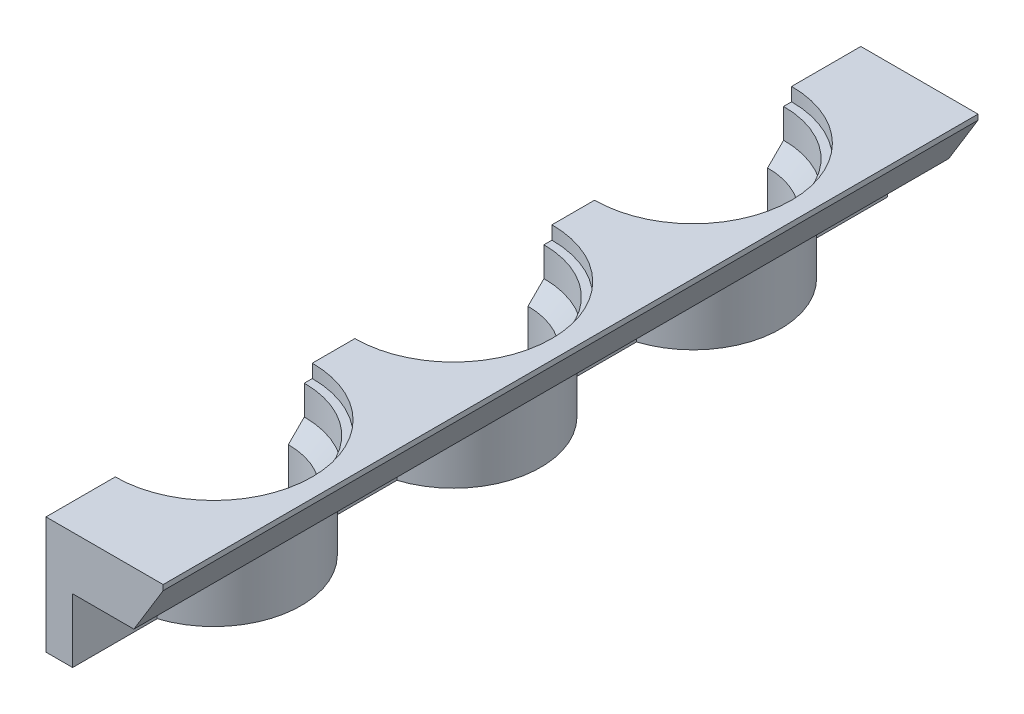
SolidWorks part; units mm, degrees
ref_plane "Płaszczyzna przednia" through (0, 0, 0) normal (0, 0, 1) x (1, 0, 0)
ref_plane "Płaszczyzna górna" through (0, 0, 0) normal (0, 1, 0) x (1, 0, 0)
ref_plane "Płaszczyzna prawa" through (0, 0, 0) normal (1, 0, 0) x (0, 0, -1)
sketch "Sketch1" plane through (0, 0, 0) normal (0, 1, 0) x (1, 0, 0)
  line L0 (0, 65.8555) -> (0, -65.8555) construction
  line L1 (0, -11.4) -> (0, -31.5)
  line L2 (0, -31.5) -> (22, -31.5)
  line L3 (104.3478, 45) -> (-104.3478, 45) construction
  line L4 (22, -31.5) -> (22, 121.5)
  line L5 (0, 101.4) -> (0, 121.5)
  line L6 (0, 121.5) -> (22, 121.5)
  line L7 (0, 11.4) -> (0, 33.6)
  line L8 (0, 56.4) -> (0, 78.6)
  arc A6 (0, -11.4) -> (0, 11.4) centre (0, 0) ccw
  arc A7 (0, 33.6) -> (0, 56.4) centre (0, 45) ccw
  arc A8 (0, 78.6) -> (0, 101.4) centre (0, 90) ccw
  point P7 (0, 0)
  point P20 (0, 45)
  point P23 (22, 45)
  dimension "D1" = 31.5
  dimension "D2" = 11.4
  dimension "D3" = 45
  dimension "D6" = 3
  dimension "D5" = 22
extrude "Boss-Extrude1" add sketch "Sketch1" against normal blind 10
sketch "Sketch3" plane through (0, -10, 0) normal (0, -1, 0) x (1, 0, 0)
  line L23 (0, -121.5) -> (0, -101.4)
  line L24 (0, -78.6) -> (0, -56.4)
  line L25 (0, -33.6) -> (0, -11.4)
  line L26 (0, 11.4) -> (0, 31.5)
  line L27 (5, -121.5) -> (5, -105.6192)
  line L28 (5, -74.3808) -> (5, -60.6192)
  line L29 (5, -29.3808) -> (5, -15.6192)
  line L30 (5, 15.6192) -> (5, 31.5)
  line L31 (5, -121.5) -> (5, -105.6192)
  line L32 (5, -74.3808) -> (5, -60.6192)
  line L33 (5, -29.3808) -> (5, -15.6192)
  line L34 (5, 15.6192) -> (5, 31.5)
  line L35 (0, 31.5) -> (5, 31.5)
  line L36 (0, -121.5) -> (5, -121.5)
  arc A15 (0, -101.4) -> (0, -78.6) centre (0, -90) ccw
  arc A16 (0, -56.4) -> (0, -33.6) centre (0, -45) ccw
  arc A17 (0, -11.4) -> (0, 11.4) centre (0, 0) ccw
  arc A18 (5, -105.6192) -> (5, -74.3808) centre (0, -90) ccw
  arc A19 (5, -60.6192) -> (5, -29.3808) centre (0, -45) ccw
  arc A20 (5, -15.6192) -> (5, 15.6192) centre (0, 0) ccw
  arc A21 (5, -105.6192) -> (5, -74.3808) centre (0, -90) ccw
  arc A22 (5, -60.6192) -> (5, -29.3808) centre (0, -45) ccw
  arc A23 (5, -15.6192) -> (5, 15.6192) centre (0, 0) ccw
  dimension "D1" = 5
extrude "Boss-Extrude2" add sketch "Sketch3" along normal blind 12
chamfer "Chamfer2" distance 5.5 distance2 9 1 edges at (22, -10, -45)
ref_plane "Plane1" through (0, 0, -75) normal (0, 0, 1) x (1, 0, 0)
sketch "Sketch6" plane through (0, 0, 0) normal (-1, 0, 0) x (0, 0, 1)
  line L0 (-101.4, 0) -> (-78.6, 0) construction
  line L1 (-76, -11) -> (-76, -26)
  line L2 (-90, 3.7296) -> (-90, -25.2968) construction
  line L3 (-90, 0) -> (-73, 0)
  line L4 (-73, 0) -> (-73, -8)
  line L5 (-90, -11) -> (-76, -11)
  line L6 (-73, -8) -> (-76, -11)
  line L7 (-90, -26) -> (-76, -26)
  line L8 (-90, 0) -> (-90, -26)
  line L10 (-90, 0) -> (-71.5, 0)
  line L11 (-90, 0) -> (-90, -2.5)
  line L12 (-90, -2.5) -> (-71.5, -2.5)
  line L13 (-71.5, 0) -> (-71.5, -2.5)
  point P3 (-90, 0)
  point P16 (-90, 0)
  dimension "D1" = 17
  dimension "D2" = 8
  dimension "D3" = 14
  dimension "D4" = 3
  dimension "D5" = 15
  dimension "D6" = 18.5
  dimension "D7" = 2.5
revolve "Cut-Revolve6" cut sketch "Sketch6" angle 360 about L8
pattern_linear "LPattern3" count 3 spacing 45 along (0, 0, 1) of "Cut-Revolve6"
sketch "Sketch7" plane through (5, 0, 0) normal (1, 0, 0) x (0, 0, -1)
  line L0 (74.3808, -10) -> (60.6192, -16) construction
  line L1 (60.6192, -22) -> (60.6192, -10) construction
  circle A0 centre (67.5, -13) radius 1.5
  point P3 (67.5, -13)
  dimension "D1" = 3
extrude "Cut-Extrude1" cut sketch "Sketch7" against normal blind 10
pattern_linear "LPattern4" count 3 spacing 45 along (0, 0, 1) of "Cut-Extrude1"
pattern_linear "LPattern5" count 2 spacing 45 along (0, 0, -1) of "Cut-Extrude1"
